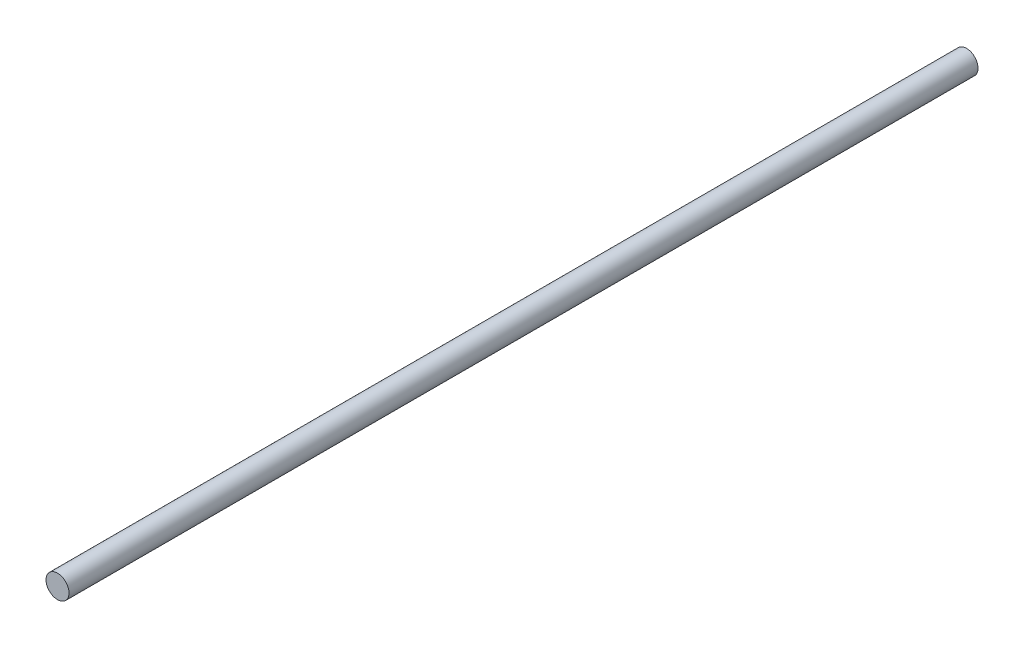
SolidWorks part; units mm, degrees
ref_plane "前视基准面" through (0, 0, 0) normal (0, 0, 1) x (1, 0, 0)
ref_plane "上视基准面" through (0, 0, 0) normal (0, 1, 0) x (1, 0, 0)
ref_plane "右视基准面" through (0, 0, 0) normal (1, 0, 0) x (0, 0, -1)
sketch "草图1" plane through (0, 0, 0) normal (0, 0, 1) x (1, 0, 0)
  circle A0 centre (0, 0) radius 10
  dimension "D1" = 20
extrude "凸台-拉伸1" add sketch "草图1" along normal blind 790
